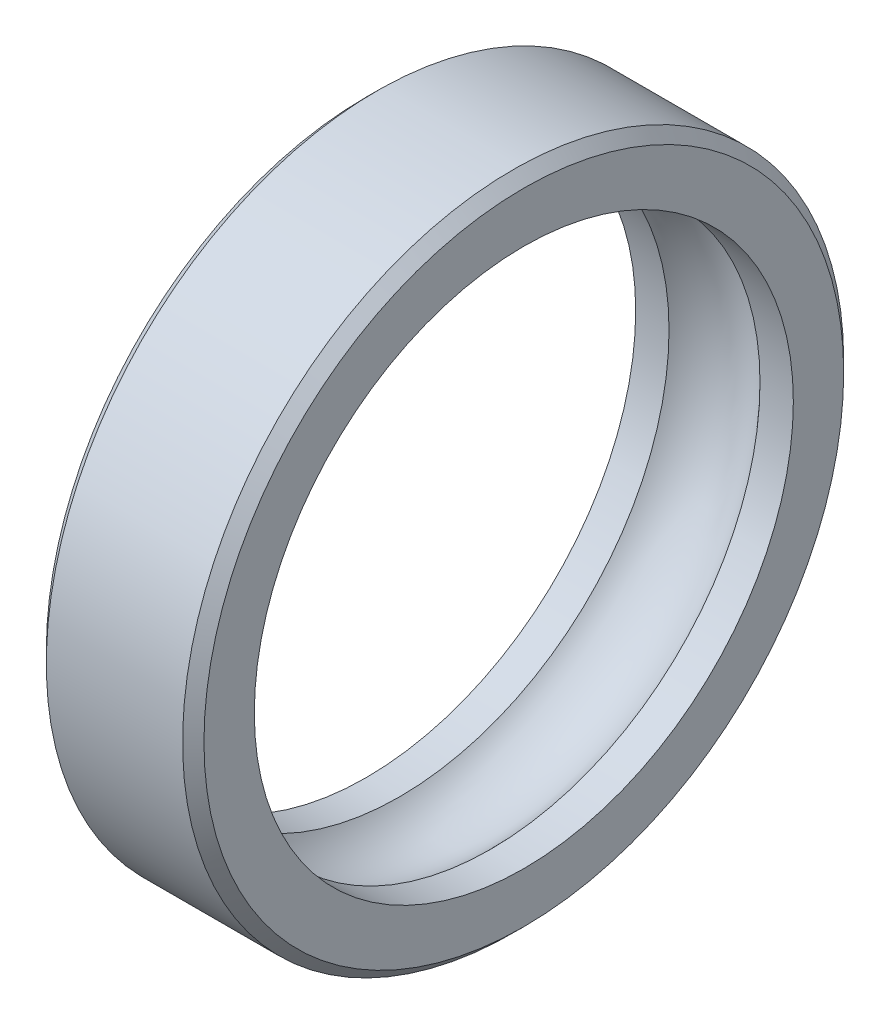
SolidWorks part; units mm, degrees
ref_plane "Front Plane" through (0, 0, 0) normal (0, 0, 1) x (1, 0, 0)
ref_plane "Top Plane" through (0, 0, 0) normal (0, 1, 0) x (1, 0, 0)
ref_plane "Right Plane" through (0, 0, 0) normal (1, 0, 0) x (0, 0, -1)
sketch "Sketch1" plane through (0, 0, 0) normal (0, 0, 1) x (1, 0, 0)
  line L0 (-76.6332, 0) -> (55.6635, 0) construction
  line L1 (-8.9443, 53) -> (-15.5, 53)
  line L2 (15.5, 65) -> (-15.5, 65)
  line L3 (15.5, 65) -> (15.5, 53)
  line L4 (15.5, 53) -> (8.9443, 53)
  line L5 (-15.5, 65) -> (-15.5, 53)
  line L6 (15.5, 65) -> (-15.5, 53) construction
  line L7 (15.5, 53) -> (-15.5, 65) construction
  arc A0 (8.9443, 53) -> (-8.9443, 53) centre (0, 45) ccw
  point P3 (0, 59)
  dimension "D6" = 12
  dimension "D1" = 53
  dimension "D2" = 65
  dimension "D3" = 31
  dimension "D4" = 0
  dimension "D5" = 8
revolve "Revolve1" add sketch "Sketch1" angle 360 about L0
chamfer "Chamfer1" distance 2.1 angle 45 2 edges at (-15.5, 0, 65) (15.5, 0, 65)
